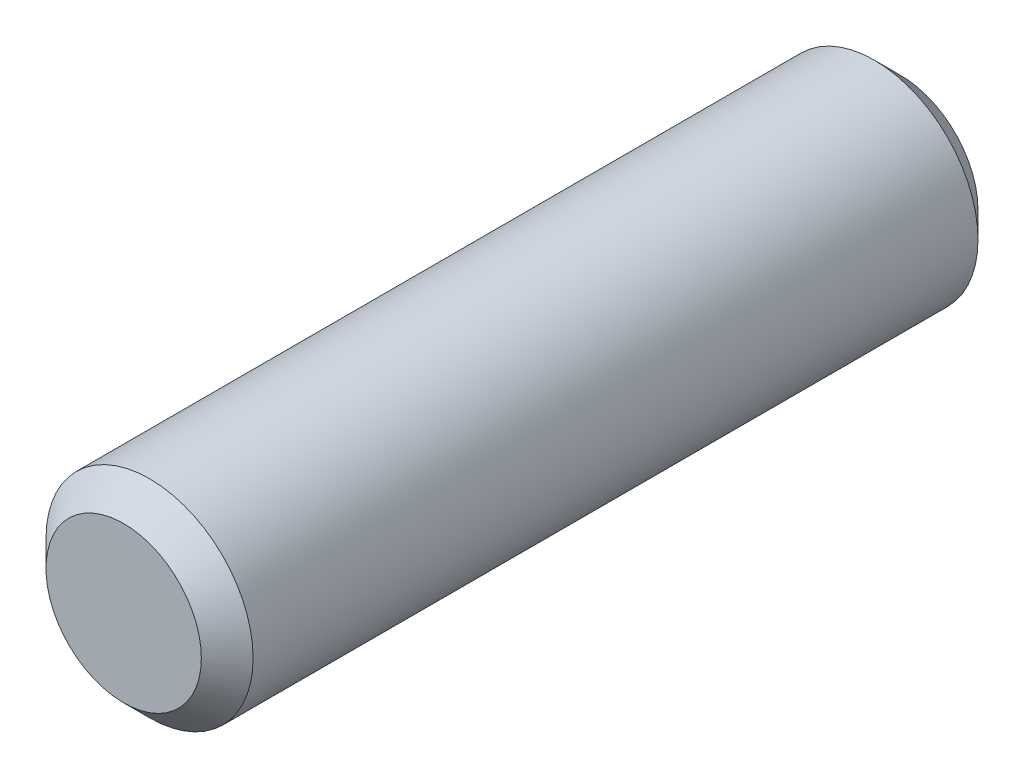
SolidWorks part; units mm, degrees
ref_plane "Front Plane" through (0, 0, 0) normal (0, 0, 1) x (1, 0, 0)
ref_plane "Top Plane" through (0, 0, 0) normal (0, 1, 0) x (1, 0, 0)
ref_plane "Right Plane" through (0, 0, 0) normal (1, 0, 0) x (0, 0, -1)
sketch "Sketch1" plane through (0, 0, 0) normal (0, 0, 1) x (1, 0, 0)
  circle A0 centre (0, 0) radius 1
  dimension "D1" = 2
extrude "Boss-Extrude1" add sketch "Sketch1" along normal blind 7.5
chamfer "Chamfer1" distance 0.25 2 edges at (1, 0, 0) (1, 0, 7.5)
